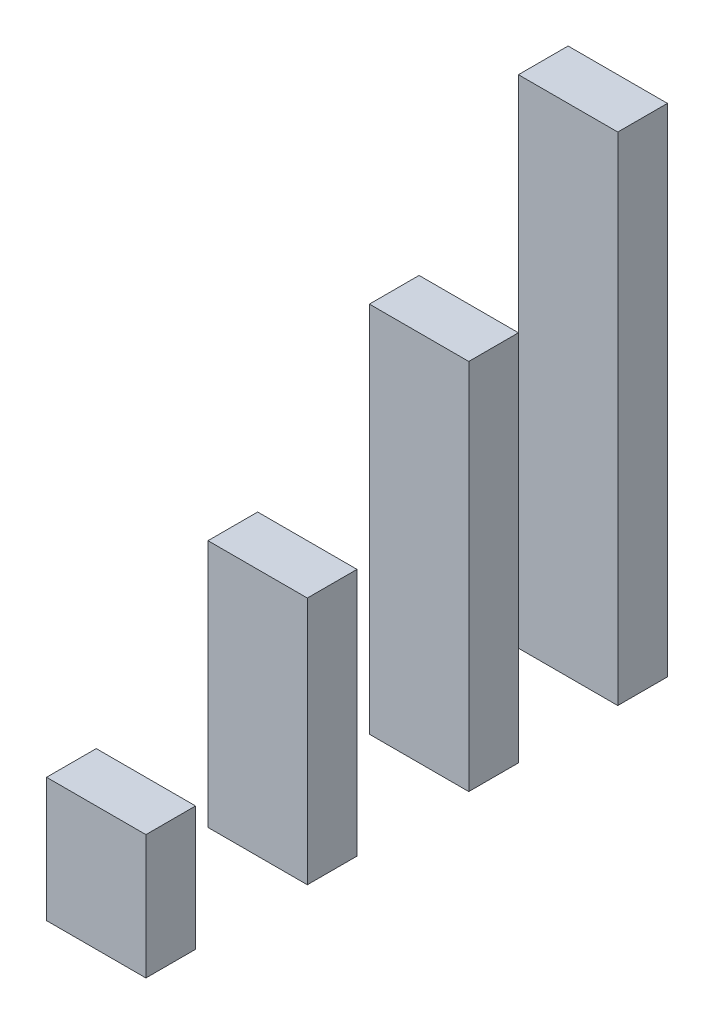
SolidWorks part; units mm, degrees
ref_plane "Front Plane" through (0, 0, 0) normal (0, 0, 1) x (1, 0, 0)
ref_plane "Top Plane" through (0, 0, 0) normal (0, 1, 0) x (1, 0, 0)
ref_plane "Right Plane" through (0, 0, 0) normal (1, 0, 0) x (0, 0, -1)
sketch "Sketch1" plane through (0, 0, 0) normal (0, 1, 0) x (1, 0, 0)
  line L1 (25, -25) -> (-25, -25)
  line L2 (25, -25) -> (25, 25)
  line L3 (25, 25) -> (-25, 25)
  line L4 (-25, -25) -> (-25, 25)
  line L5 (25, -25) -> (-25, 25) construction
  line L6 (25, 25) -> (-25, -25) construction
  point P0 (0, 0)
  dimension "D1" = 50
  dimension "D2" = 50
ref_plane "Plane1" through (0, 1, 0) normal (0, 1, 0) x (1, 0, 0)
sketch "Sketch2" plane through (0, 1, 0) normal (0, 1, 0) x (1, 0, 0)
  line L0 (25, -25) -> (-25, -25) construction
  line L1 (4, -21) -> (-4, -21)
  line L2 (4, -21) -> (4, -17)
  line L3 (4, -17) -> (-4, -17)
  line L4 (-4, -21) -> (-4, -17)
  line L5 (25, -25) -> (25, 25) construction
  dimension "D1" = 4
  dimension "D2" = 8
  dimension "D3" = 4
  dimension "D4" = 21
extrude "Boss-Extrude1" add sketch "Sketch2" along normal blind 10
sketch "Sketch3" plane through (0, 1, 0) normal (0, 1, 0) x (1, 0, 0)
  line L1 (-4, -4) -> (4, -4)
  line L2 (-4, -4) -> (-4, -8)
  line L3 (-4, -8) -> (4, -8)
  line L4 (4, -4) -> (4, -8)
  line L5 (4, -17) -> (-4, -17) construction
  line L7 (-25, -25) -> (-25, 25) construction
  dimension "D1" = 9
  dimension "D2" = 4
  dimension "D3" = 8
  dimension "D4" = 21
extrude "Boss-Extrude2" add sketch "Sketch3" along normal blind 20 separate body
sketch "Sketch4" plane through (0, 1, 0) normal (0, 1, 0) x (1, 0, 0)
  line L0 (-25, -25) -> (-25, 25) construction
  line L1 (-4, 9) -> (4, 9)
  line L2 (-4, 9) -> (-4, 5)
  line L3 (-4, 5) -> (4, 5)
  line L4 (4, 9) -> (4, 5)
  line L5 (4, -4) -> (-4, -4) construction
  dimension "D1" = 4
  dimension "D2" = 8
  dimension "D3" = 21
  dimension "D4" = 9
extrude "Boss-Extrude3" add sketch "Sketch4" along normal blind 30 separate body
sketch "Sketch5" plane through (0, 1, 0) normal (0, 1, 0) x (1, 0, 0)
  line L0 (-25, -25) -> (-25, 25) construction
  line L1 (-4, 21) -> (4, 21)
  line L2 (-4, 21) -> (-4, 17)
  line L3 (-4, 17) -> (4, 17)
  line L4 (4, 21) -> (4, 17)
  line L6 (25, 25) -> (-25, 25) construction
  dimension "D1" = 4
  dimension "D2" = 8
  dimension "D3" = 21
  dimension "D4" = 4
extrude "Boss-Extrude4" add sketch "Sketch5" along normal blind 40 separate body
